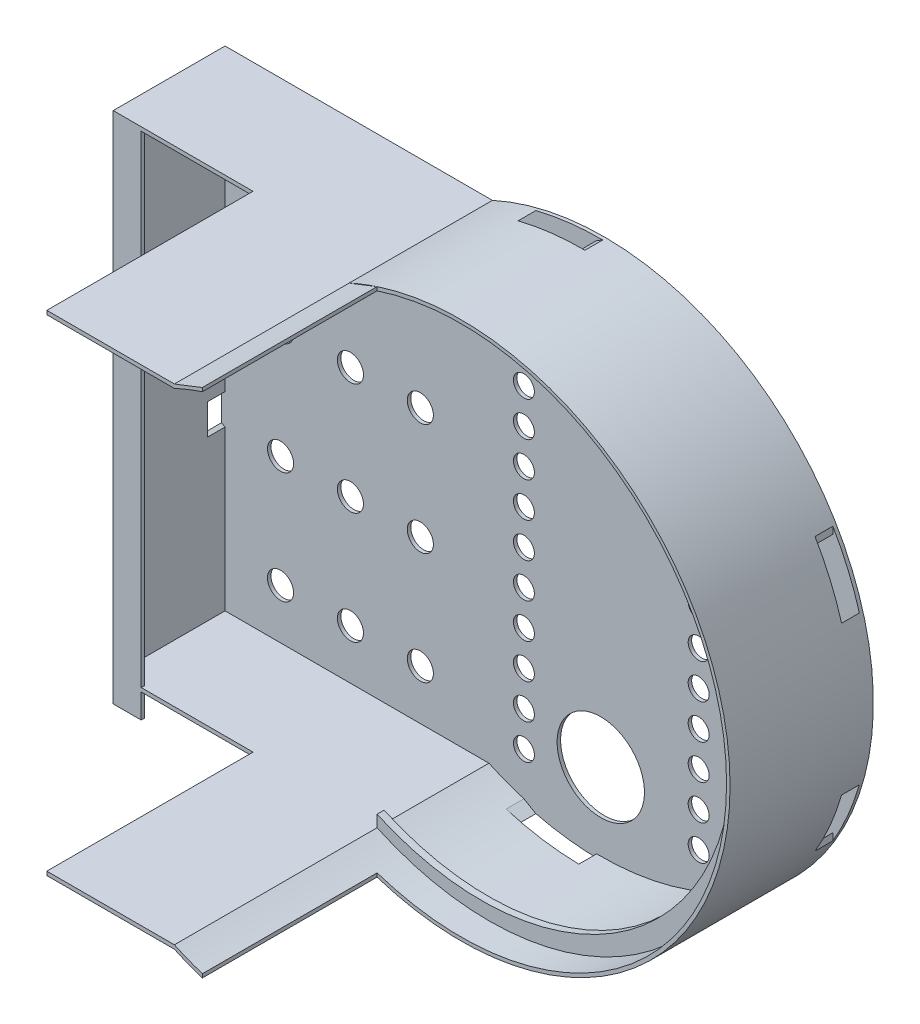
SolidWorks part; units mm, degrees
ref_plane "Front Plane" through (0, 0, 0) normal (0, 0, 1) x (1, 0, 0)
ref_plane "Top Plane" through (0, 0, 0) normal (0, 1, 0) x (1, 0, 0)
ref_plane "Right Plane" through (0, 0, 0) normal (1, 0, 0) x (0, 0, -1)
sketch "Sketch1" plane through (0, 0, 0) normal (0, 0, 1) x (1, 0, 0)
  circle A1 centre (0, 0) radius 77
  dimension "D2" = 154
extrude "Boss-Extrude1" add sketch "Sketch1" along normal blind 10
sketch "Sketch2" plane through (0, 0, 10) normal (0, 0, 1) x (1, 0, 0)
  circle A0 centre (0, 0) radius 76
  dimension "D1" = 152
extrude "Cut-Extrude1" cut sketch "Sketch2" against normal blind 8
sketch "Sketch3" plane through (0, 0, 0) normal (0, 0, -1) x (-1, 0, 0)
  circle A0 centre (0, 0) radius 77
  circle A1 centre (0, 0) radius 76
  dimension "D1" = 152
extrude "Boss-Extrude2" add sketch "Sketch3" along normal blind 30
ref_plane "Plane1" through (0, 0, -30) normal (0, 0, -1) x (-1, 0, 0)
sketch "Sketch4" plane through (0, 0, -30) normal (0, 0, -1) x (-1, 0, 0)
  circle A0 centre (0, 0) radius 77
extrude "Boss-Extrude3" add sketch "Sketch4" along normal blind 1
sketch "Sketch5" plane through (0, 0, -31) normal (0, 0, -1) x (-1, 0, 0)
  line L0 (77, 0) -> (77, 87.2498) construction
  line L2 (77, 84.6415) -> (32, 84.6415)
  line L3 (77, 84.6415) -> (77, -79.1639)
  line L4 (77, -79.1639) -> (32, -79.1639)
  line L5 (32, 84.6415) -> (32, -79.1639)
  circle A0 centre (0, 0) radius 77 construction
  dimension "D1" = 45
extrude "Cut-Extrude3" cut sketch "Sketch5" against normal through all
sketch "Sketch8" plane through (-32, 0, 0) normal (-1, 0, 0) x (0, 0, 1)
  line L1 (-31, 70.0357) -> (10, 70.0357) construction
  line L2 (2, -76) -> (2, 76) construction
  line L3 (2, 70.0357) -> (-31, 70.0357)
  line L4 (-31, 70.0357) -> (-31, -70.0357)
  line L5 (-31, -70.0357) -> (2, -70.0357)
  line L6 (10, -70.0357) -> (-31, -70.0357) construction
  line L8 (2, -68.9348) -> (-30, -68.9348)
  line L9 (-30, -68.9348) -> (-30, 68.9348)
  line L10 (-30, 68.9348) -> (2, 68.9348)
  line L14 (2, 70.0357) -> (10, 70.0357)
  line L15 (10, 70.0357) -> (10, 68.9348)
  line L16 (10, 68.9348) -> (2, 68.9348)
  line L17 (2, -68.9348) -> (10, -68.9348)
  line L18 (10, -68.9348) -> (10, -70.0357)
  line L19 (10, -70.0357) -> (2, -70.0357)
extrude "Boss-Extrude4" add sketch "Sketch8" along normal blind 36.5
sketch "Sketch9" plane through (0, 0, 2) normal (0, 0, 1) x (1, 0, 0)
  circle A0 centre (0, 53.9238) radius 12.5
  dimension "D1" = 25
extrude "Cut-Extrude4" cut sketch "Sketch9" against normal through all contours A0
pattern_circular "CirPattern1" count 3 every 90 about axis through (0, 0, 0) along (0, 0, 1) of "Cut-Extrude4"
sketch "Sketch10" plane through (0, 0, 10) normal (0, 0, 1) x (1, 0, 0)
  line L0 (-68.5, 70.0357) -> (-68.5, 68.9348)
  line L1 (-68.5, 68.9348) -> (-32, 68.9348)
  line L2 (-68.5, 70.0357) -> (-32, 70.0357)
  line L3 (-68.5, -68.9348) -> (-68.5, -70.0357)
  line L4 (-68.5, -70.0357) -> (-32, -70.0357)
  line L5 (-32, -68.9348) -> (-68.5, -68.9348)
  line L6 (-24.0003, -73.1641) -> (-24.0003, -72.1109)
  line L7 (-24.0003, 73.1641) -> (-24.0003, 72.1109)
  arc A0 (-24.0003, 72.1109) -> (-32, 68.9348) centre (0, 0) ccw
  arc A1 (-32, -68.9348) -> (-32, 68.9348) centre (0, 0) ccw construction
  arc A2 (-32, -70.0357) -> (-32, 70.0357) centre (0, 0) ccw construction
  arc A3 (-24.0003, 73.1641) -> (-32, 70.0357) centre (-206.4522, 527.9236) cw
  arc A4 (-24.0003, -72.1109) -> (-32, -68.9348) centre (0, 0) cw
  arc A5 (-32, -68.9348) -> (-32, 68.9348) centre (0, 0) ccw construction
  arc A6 (-24.0003, -73.1641) -> (-32, -70.0357) centre (0, 0) cw
extrude "Boss-Extrude5" add sketch "Sketch10" along normal blind 50
sketch "Sketch11" plane through (-68.5, 0, 0) normal (-1, 0, 0) x (0, 0, 1)
  line L0 (0, 68.9348) -> (0, 70.0357)
  line L1 (-31, 70.0357) -> (10, 70.0357) construction
  line L2 (0, 76) -> (0, -76) construction
  line L3 (0, 70.0357) -> (-31, 70.0357)
  line L4 (-31, 70.0357) -> (-31, -70.0357)
  line L5 (-31, -70.0357) -> (0, -70.0357)
  line L6 (-31, -70.0357) -> (60, -70.0357) construction
  line L7 (60, -70.0357) -> (-31, -70.0357) construction
  line L8 (0, -70.0357) -> (0, -68.9348)
  line L9 (0, -68.9348) -> (-30, -68.9348)
  line L10 (-30, -68.9348) -> (-30, 68.9348)
  line L11 (-30, 68.9348) -> (0, 68.9348)
extrude "Boss-Extrude6" add sketch "Sketch11" along normal blind 40
sketch "Sketch12" plane through (0, 68.9348, 0) normal (0, -1, 0) x (1, 0, 0)
  line L0 (-108.5, -31) -> (-32, -31) construction
  line L1 (-108.5, 0) -> (-107.5, 0)
  line L2 (-108.5, 0) -> (-108.5, -31)
  line L3 (-108.5, -31) -> (-107.5, -31)
  line L4 (-107.5, 0) -> (-107.5, -31)
  dimension "D1" = 1
extrude "Boss-Extrude8" add sketch "Sketch12" along normal up to next
sketch "Sketch13" plane through (0, 0, 2) normal (0, 0, 1) x (1, 0, 0)
  circle A0 centre (0, 0) radius 27.1984
extrude "Cut-Extrude6" cut sketch "Sketch13" against normal up to next
sketch "Sketch14" plane through (0, 0, -30) normal (0, 0, 1) x (1, 0, 0)
  circle A0 centre (-21.9913, 59.5686) radius 3
  dimension "D1" = 6
extrude "Cut-Extrude7" cut sketch "Sketch14" against normal up to next
pattern_linear "LPattern1" count 13 spacing 10 along (0, -1, 0) of "Cut-Extrude7"
pattern_linear "LPattern5" count 2 spacing 50 along (1, 0, 0) of "LPattern1", "Cut-Extrude7"
sketch "Sketch15" plane through (-68.5, 0, 0) normal (-1, 0, 0) x (0, 0, 1)
  line L0 (60, -70.0357) -> (-31, -70.0357) construction
  line L1 (0, -68.9348) -> (1, -68.9348)
  line L2 (0, -68.9348) -> (0, -70.0357)
  line L3 (0, -70.0357) -> (1, -70.0357)
  line L4 (1, -68.9348) -> (1, -70.0357)
  line L5 (-31, 70.0357) -> (10, 70.0357) construction
  line L6 (0, 68.9348) -> (1, 68.9348)
  line L7 (0, 68.9348) -> (0, 70.0357)
  line L8 (0, 70.0357) -> (1, 70.0357)
  line L9 (1, 68.9348) -> (1, 70.0357)
  dimension "D1" = 1
  dimension "D2" = 1
extrude "Boss-Extrude9" add sketch "Sketch15" along normal blind 40
sketch "Sketch16" plane through (0, 0, 2) normal (0, 0, 1) x (1, 0, 0)
  line L0 (-32, -68.9348) -> (-32, 68.9348) construction
  line L1 (-32, 65.2613) -> (-32, -65.5743)
  arc A0 (-32, 65.2613) -> (-32, -65.5743) centre (-2.2459, -0.1565) cw
extrude "Cut-Extrude8" cut sketch "Sketch16" against normal blind 10
sketch "Sketch17" plane through (0, 0, 0) normal (0, 1, 0) x (1, 0, 0)
  line L0 (55, 30) -> (-55, 30) construction
  line L1 (66.3998, 30) -> (74, 30)
  line L2 (66.3998, 30) -> (66.3998, 24.9086)
  line L3 (66.3998, 24.9086) -> (74, 24.9086)
  line L4 (74, 30) -> (74, 24.9086)
  line L5 (77, 31) -> (-32, 31) construction
  line L6 (77, -10) -> (77, 31) construction
  dimension "D1" = 1
  dimension "D2" = 3
extrude "Cut-Extrude9" cut sketch "Sketch17" against normal through all both and the other way through all
pattern_circular "CirPattern2" count 3 every 120 about axis through (0, 0, 0) along (0, 0, 1) of "Cut-Extrude9"
sketch "Sketch19" plane through (0, 68.9348, 0) normal (0, -1, 0) x (1, 0, 0)
  line L1 (-108.5, 1) -> (-100.5, 1)
  line L2 (-108.5, 1) -> (-108.5, 0)
  line L3 (-108.5, 0) -> (-100.5, 0)
  line L4 (-100.5, 1) -> (-100.5, 0)
  dimension "D1" = 8
extrude "Boss-Extrude10" add sketch "Sketch19" along normal through all
sketch "Sketch20" plane through (0, 0, -30) normal (0, 0, 1) x (1, 0, 0)
  circle A0 centre (-91.6287, 9.3285) radius 3.7342
extrude "Cut-Extrude10" cut sketch "Sketch20" against normal through all both and the other way through all
pattern_linear "LPattern6" count 3 spacing 20 along (1, 0, 0) of "Cut-Extrude10"
pattern_linear "LPattern7" count 3 spacing 32 along (0, -1, 0) of "LPattern6", "Cut-Extrude10"
